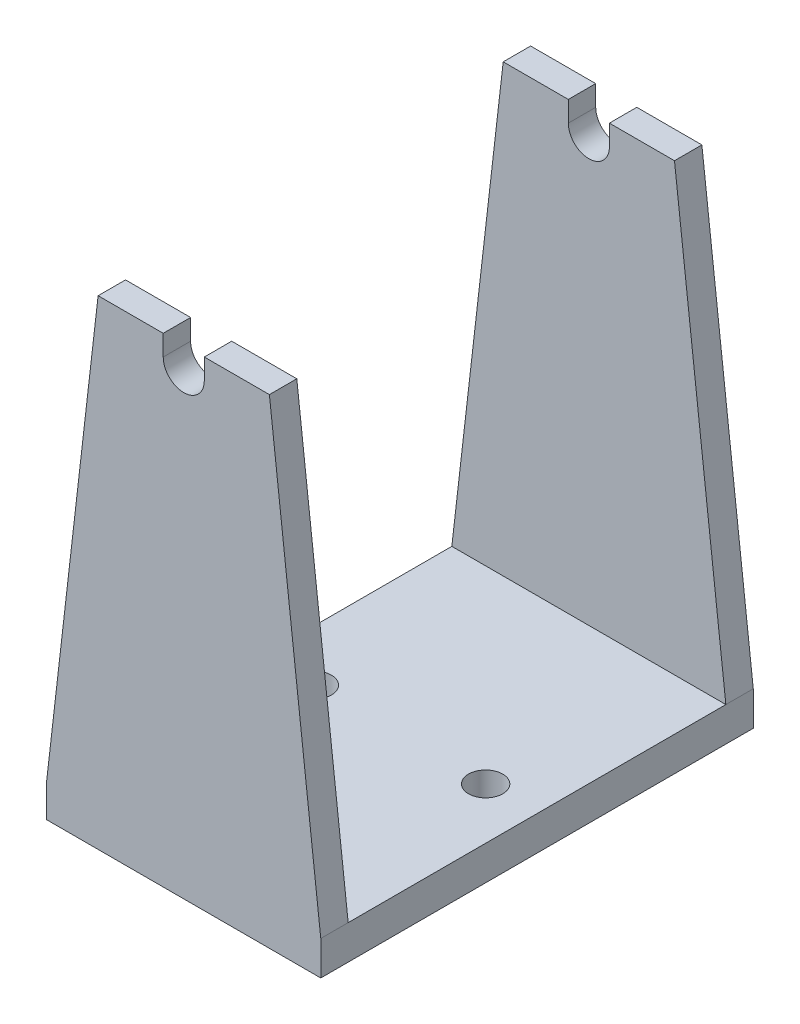
SolidWorks part; units mm, degrees
ref_plane "Piano frontale" through (0, 0, 0) normal (0, 0, 1) x (1, 0, 0)
ref_plane "Piano superiore" through (0, 0, 0) normal (0, 1, 0) x (1, 0, 0)
ref_plane "Piano destro" through (0, 0, 0) normal (1, 0, 0) x (0, 0, -1)
sketch "Schizzo1" plane through (0, 0, 0) normal (0, 0, 1) x (1, 0, 0)
  line L0 (0, 0) -> (0, 59.8848) construction
  line L1 (-20, 0) -> (20, 0)
  line L2 (20, 0) -> (20, 5)
  line L3 (20, 5) -> (12.5, 70)
  line L4 (12.5, 70) -> (2.9978, 70)
  line L5 (-12.5, 70) -> (-2.9978, 70)
  line L6 (-20, 5) -> (-12.5, 70)
  line L7 (-20, 0) -> (-20, 5)
  line L8 (2.9978, 70) -> (2.9978, 67)
  line L9 (-2.9978, 70) -> (-2.9978, 67)
  arc A0 (-2.9978, 67) -> (2.9978, 67) centre (0, 67) ccw
  dimension "D2" = 2.9978
  dimension "D1" = 40
  dimension "D3" = 25
  dimension "D4" = 5
  dimension "D5" = 70
  dimension "D6" = 3
extrude "Estrusione-Estrusione1" add sketch "Schizzo1" along normal blind 4
sketch "Schizzo2" plane through (0, 0, 4) normal (0, 0, 1) x (1, 0, 0)
  line L1 (-20, 5) -> (20, 5)
  line L2 (-20, 5) -> (-20, 0)
  line L3 (-20, 0) -> (20, 0)
  line L4 (20, 5) -> (20, 0)
extrude "Estrusione-Estrusione2" add sketch "Schizzo2" along normal blind 55.13
sketch "Schizzo3" plane through (0, 0, 59.13) normal (0, 0, 1) x (1, 0, 0)
  line L7 (20, 5) -> (12.5, 70)
  line L8 (20, 0) -> (20, 5)
  line L9 (-20, 0) -> (20, 0)
  line L10 (-20, 5) -> (-20, 0)
  line L11 (-12.5, 70) -> (-20, 5)
  line L12 (-2.9978, 70) -> (-12.5, 70)
  line L13 (12.5, 70) -> (2.9978, 70)
  line L14 (20, 5) -> (12.5, 70)
  line L15 (20, 0) -> (20, 5)
  line L16 (-20, 0) -> (20, 0)
  line L17 (-20, 5) -> (-20, 0)
  line L18 (-12.5, 70) -> (-20, 5)
  line L19 (-2.9978, 70) -> (-12.5, 70)
  line L20 (12.5, 70) -> (2.9978, 70)
  line L23 (-2.9978, 67) -> (-2.9978, 70)
  line L24 (-2.9978, 67) -> (-2.9978, 70)
  line L25 (2.9978, 70) -> (2.9978, 67)
  line L26 (2.9978, 70) -> (2.9978, 67)
  arc A1 (-2.9978, 67) -> (2.9978, 67) centre (0, 67) ccw
  arc A2 (-2.9978, 67) -> (2.9978, 67) centre (0, 67) ccw
  dimension "D1" = 0
extrude "Estrusione-Estrusione3" add sketch "Schizzo3" along normal blind 4
sketch "Schizzo4" plane through (0, 5, 0) normal (0, 1, 0) x (1, 0, 0)
  line L0 (-20, -31.565) -> (20, -31.565) construction
  line L1 (-20, -59.13) -> (-20, -4) construction
  line L2 (20, -59.13) -> (20, -4) construction
  line L3 (0, -31.565) -> (0, -51.2971) construction
  circle A0 centre (12.5, -31.565) radius 2.5
  circle A1 centre (-12.5, -31.565) radius 2.5
  dimension "D1" = 5
  dimension "D2" = 25
extrude "Taglio-Estrusione1" cut sketch "Schizzo4" against normal through all
